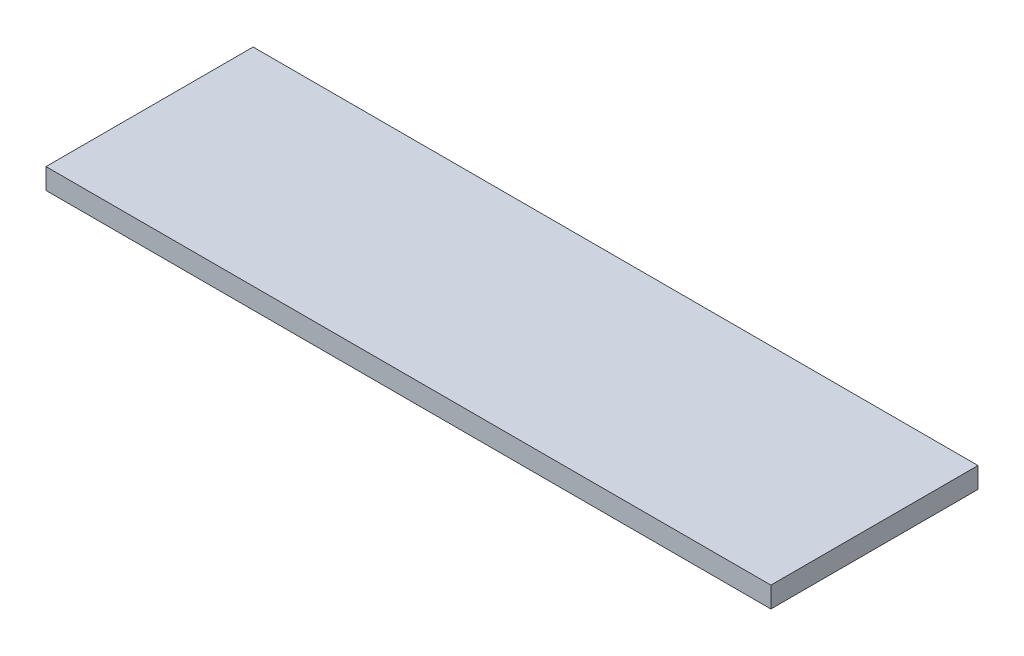
SolidWorks part; units mm, degrees
ref_plane "Front Plane" through (0, 0, 0) normal (0, 0, 1) x (1, 0, 0)
ref_plane "Top Plane" through (0, 0, 0) normal (0, 1, 0) x (1, 0, 0)
ref_plane "Right Plane" through (0, 0, 0) normal (1, 0, 0) x (0, 0, -1)
sketch "Sketch1" plane through (0, 0, 0) normal (0, 1, 0) x (1, 0, 0)
  line L1 (-35, -10) -> (35, -10)
  line L2 (-35, -10) -> (-35, 10)
  line L3 (-35, 10) -> (35, 10)
  line L4 (35, -10) -> (35, 10)
  line L5 (-35, -10) -> (35, 10) construction
  line L6 (-35, 10) -> (35, -10) construction
  point P0 (0, 0)
  dimension "D1" = 20
  dimension "D2" = 70
extrude "Boss-Extrude1" add sketch "Sketch1" along normal blind 2
